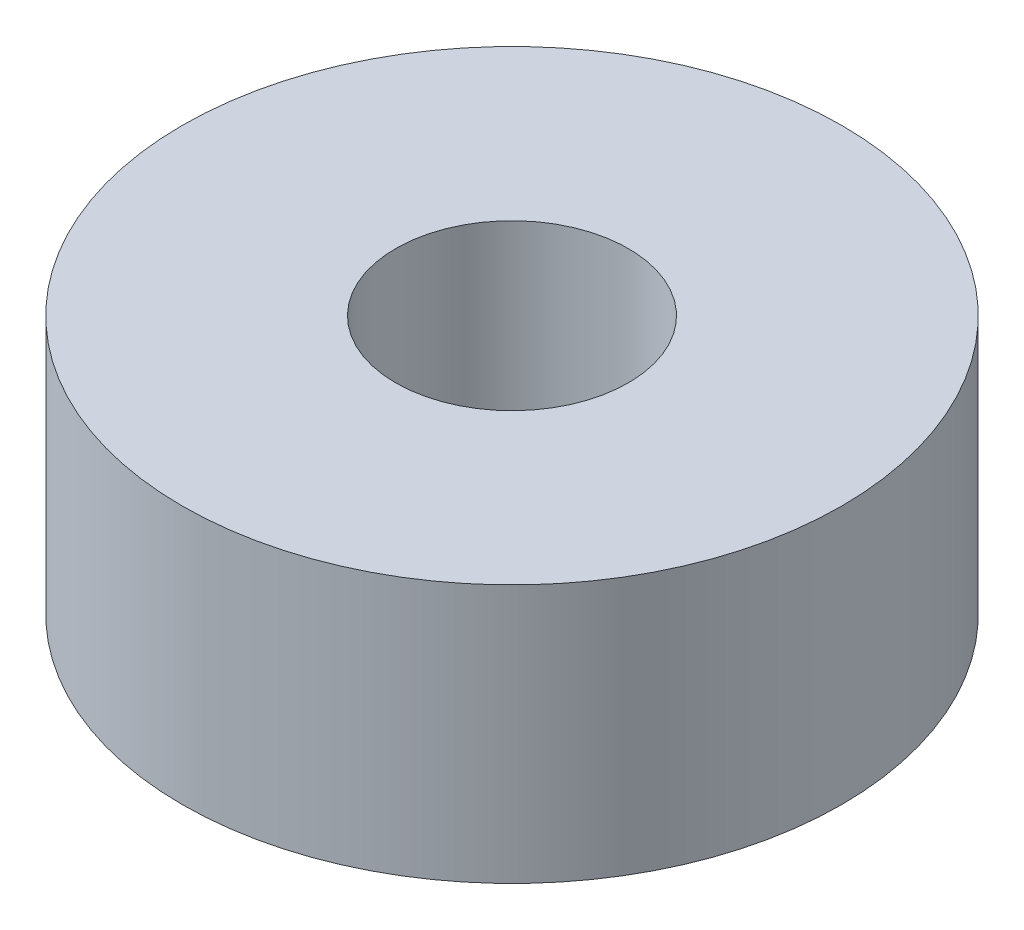
SolidWorks part; units mm, degrees
ref_plane "Front Plane" through (0, 0, 0) normal (0, 0, 1) x (1, 0, 0)
ref_plane "Top Plane" through (0, 0, 0) normal (0, 1, 0) x (1, 0, 0)
ref_plane "Right Plane" through (0, 0, 0) normal (1, 0, 0) x (0, 0, -1)
sketch "Sketch1" plane through (0, 0, 0) normal (0, 1, 0) x (1, 0, 0)
  circle A0 centre (0, 0) radius 12.75
  dimension "D1" = 25.5
extrude "Boss-Extrude1" add sketch "Sketch1" along normal blind 10
sketch "Sketch2" plane through (0, 10, 0) normal (0, 1, 0) x (1, 0, 0)
  circle A0 centre (0, 0) radius 4.5
  dimension "D1" = 9
extrude "Cut-Extrude1" cut sketch "Sketch2" against normal blind 7
sketch "Sketch3" plane through (0, 0, 0) normal (0, -1, 0) x (1, 0, 0)
  line L0 (0, 0) -> (0, 12.75) construction
  circle A0 centre (0, 8.5) radius 2.5
  circle A1 centre (0, 0) radius 12.75 construction
  point P8 (0, 0)
  dimension "D2" = 5
  dimension "D1" = 8.5
extrude "Cut-Extrude2" cut sketch "Sketch3" against normal blind 7
